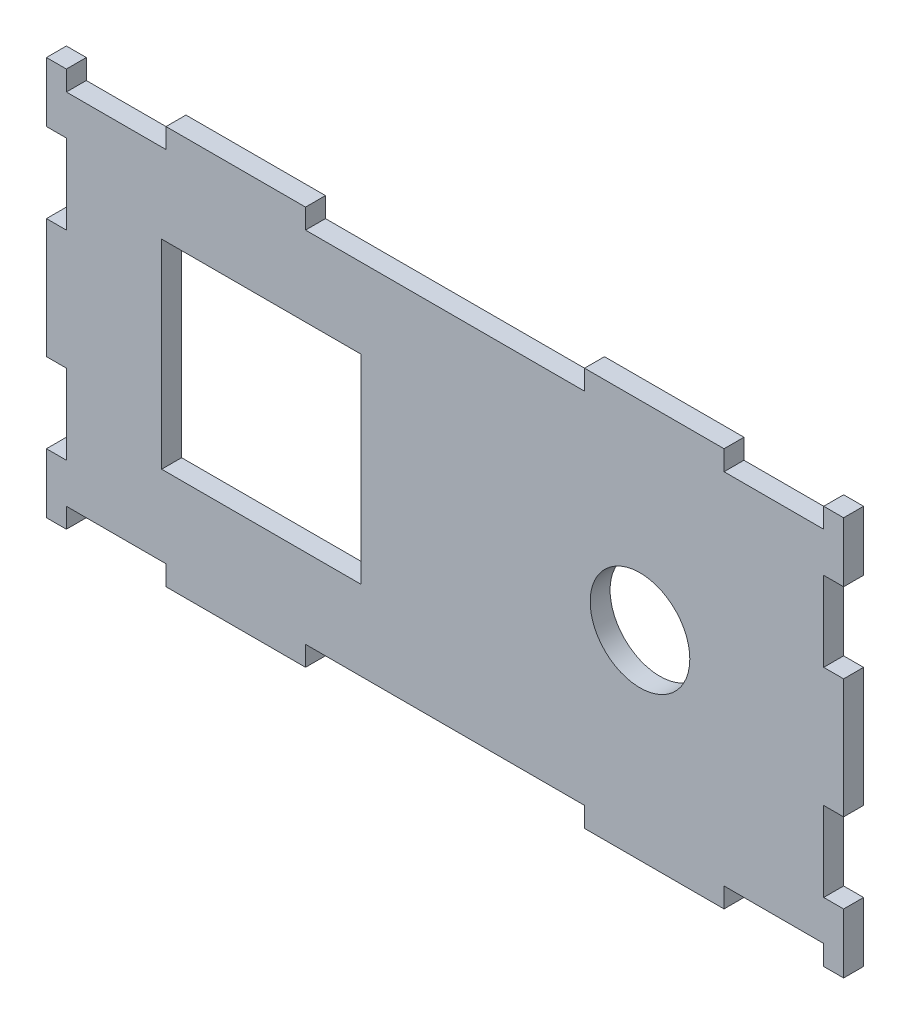
SolidWorks part; units mm, degrees
ref_plane "Plan de face" through (0, 0, 0) normal (0, 0, 1) x (1, 0, 0)
ref_plane "Plan de dessus" through (0, 0, 0) normal (0, 1, 0) x (1, 0, 0)
ref_plane "Plan de droite" through (0, 0, 0) normal (1, 0, 0) x (0, 0, -1)
sketch "Esquisse1" plane through (0, 0, 0) normal (0, 0, 1) x (1, 0, 0)
  line L0 (-28.9098, 20) -> (-23.9098, 20)
  line L1 (-23.9098, 20) -> (-23.9098, 15)
  line L2 (-23.9098, 15) -> (1.0902, 15)
  line L3 (1.0902, 15) -> (1.0902, 20)
  line L4 (1.0902, 20) -> (36.0902, 20)
  line L5 (36.0902, 20) -> (36.0902, 15)
  line L6 (36.0902, 15) -> (106.0902, 15)
  line L7 (-28.9098, 20) -> (-28.9098, 5)
  line L11 (-28.9098, -14.9983) -> (-28.9098, -44.9983)
  line L12 (71.0902, 15) -> (71.0902, -29.9983) construction
  line L13 (71.0902, -29.9983) -> (-28.9098, -29.9983) construction
  line L14 (171.0902, -14.9983) -> (171.0902, -44.9983)
  line L18 (171.0902, 20) -> (171.0902, 5.0017)
  line L19 (106.0902, 20) -> (106.0902, 15)
  line L20 (141.0902, 20) -> (106.0902, 20)
  line L21 (141.0902, 15) -> (141.0902, 20)
  line L22 (166.0902, 15) -> (141.0902, 15)
  line L23 (166.0902, 20) -> (166.0902, 15)
  line L24 (171.0902, 20) -> (166.0902, 20)
  line L25 (171.0902, -79.9966) -> (166.0902, -79.9966)
  line L26 (166.0902, -79.9966) -> (166.0902, -74.9966)
  line L27 (166.0902, -74.9966) -> (141.0902, -74.9966)
  line L28 (141.0902, -74.9966) -> (141.0902, -79.9966)
  line L29 (141.0902, -79.9966) -> (106.0902, -79.9966)
  line L30 (106.0902, -79.9966) -> (106.0902, -74.9966)
  line L31 (171.0902, -79.9966) -> (171.0902, -64.9983)
  line L32 (171.0902, -64.9983) -> (166.0902, -64.9983)
  line L33 (166.0902, -64.9983) -> (166.0902, -44.9983)
  line L34 (166.0902, -44.9983) -> (171.0902, -44.9983)
  line L35 (-23.9098, -44.9983) -> (-28.9098, -44.9983)
  line L36 (-23.9098, -59.9966) -> (-23.9098, -44.9983)
  line L38 (-28.9098, -79.9966) -> (-28.9098, -64.9983)
  line L39 (36.0902, -74.9966) -> (106.0902, -74.9966)
  line L40 (36.0902, -79.9966) -> (36.0902, -74.9966)
  line L41 (1.0902, -79.9966) -> (36.0902, -79.9966)
  line L42 (1.0902, -74.9966) -> (1.0902, -79.9966)
  line L43 (-23.9098, -74.9966) -> (1.0902, -74.9966)
  line L44 (-23.9098, -79.9966) -> (-23.9098, -74.9966)
  line L45 (-28.9098, -79.9966) -> (-23.9098, -79.9966)
  line L46 (-28.9098, 5) -> (-23.9098, 5)
  line L49 (-23.9098, 5) -> (-23.9098, -14.9983)
  line L51 (171.0902, 5.0017) -> (166.0902, 5.0017)
  line L56 (-23.9098, -14.9983) -> (-28.9098, -14.9983)
  line L58 (166.0902, -14.9983) -> (171.0902, -14.9983)
  line L59 (166.0902, 5.0017) -> (166.0902, -14.9983)
  line L60 (-23.9098, -59.9966) -> (-23.9098, -64.9983)
  line L61 (-23.9098, -64.9983) -> (-28.9098, -64.9983)
  line L62 (0, -54.9983) -> (0, -4.9983)
  line L63 (0, -4.9983) -> (50, -4.9983)
  line L64 (50, -4.9983) -> (50, -54.9983)
  line L65 (0, -54.9983) -> (50, -54.9983)
  circle A0 centre (120, -29.9983) radius 12.5
  point P29 (171.0902, -29.9983)
  point P57 (50, -29.9983)
  point P60 (0, -29.9983)
  dimension "D3" = 25
  dimension "D1" = 20
  dimension "D2" = 15
  dimension "D4" = 25
  dimension "D5" = 35
  dimension "D6" = 35
  dimension "D7" = 5
  dimension "D8" = 50
  dimension "D9" = 25
  dimension "D10" = 70
extrude "Boss.-Extru.1" add sketch "Esquisse1" along normal blind 5
